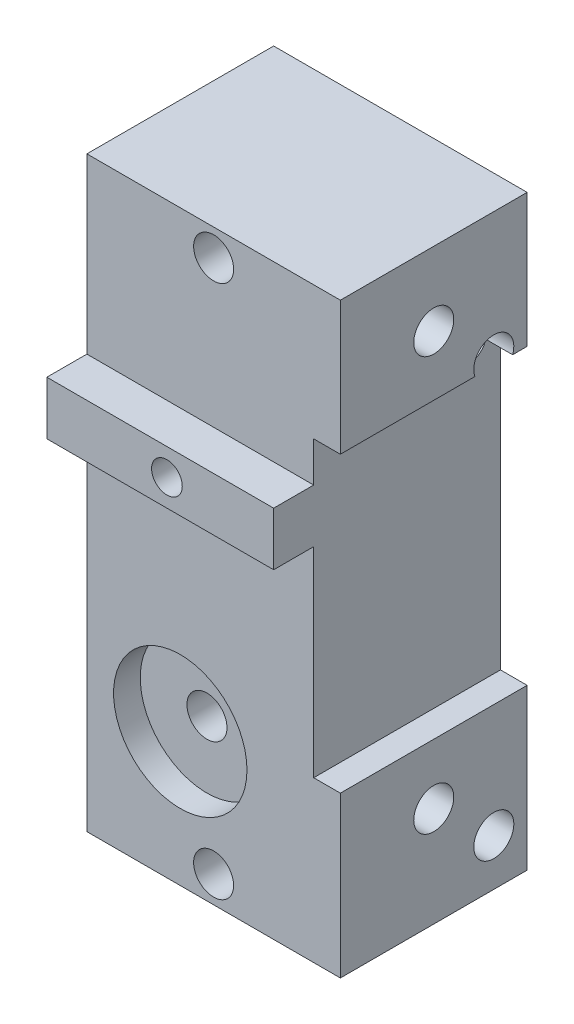
SolidWorks part; units mm, degrees
ref_plane "Front Plane" through (0, 0, 0) normal (0, 0, 1) x (1, 0, 0)
ref_plane "Top Plane" through (0, 0, 0) normal (0, 1, 0) x (1, 0, 0)
ref_plane "Right Plane" through (0, 0, 0) normal (1, 0, 0) x (0, 0, -1)
sketch "Sketch1" plane through (0, 0, 0) normal (0, 0, 1) x (1, 0, 0)
  line L0 (9.5, 0) -> (-9.5, 0)
  line L1 (-9.5, 0) -> (-9.5, 44)
  line L2 (0, 0) -> (0, 74.8611) construction
  line L3 (-9.5, 44) -> (9.5, 44)
  line L4 (9.5, 0) -> (9.5, 44)
  point P8 (0, 44)
  dimension "D1" = 9.5
  dimension "D2" = 44
extrude "Boss-Extrude1" add sketch "Sketch1" along normal blind 14
sketch "Sketch2" plane through (0, 0, 0) normal (0, 0, 1) x (1, 0, 0)
  line L0 (0, 0) -> (0, 44) construction
  line L1 (-9.5, 0) -> (9.5, 0) construction
  line L2 (9.5, 44) -> (-9.5, 44) construction
  line L3 (0, 22) -> (-9.5, 22) construction
  line L4 (-9.5, 44) -> (-9.5, 0) construction
  circle A0 centre (0, 2) radius 1.5
  circle A1 centre (0, 42) radius 1.5
  point P10 (0, 2)
  dimension "D2" = 3
  dimension "D1" = 2
extrude "Cut-Extrude1" cut sketch "Sketch2" against normal through all and the other way through all
sketch "Sketch3" plane through (0, 0, 0) normal (1, 0, 0) x (0, 0, -1)
  line L0 (-14, 0) -> (-7, 0) construction
  line L1 (-14, 0) -> (0, 0) construction
  line L2 (-7, 0) -> (-7, 7.5) construction
  line L3 (-7, 44) -> (-7, 38.5) construction
  line L4 (0, 3.5) -> (-2.5, 3.5) construction
  line L5 (-14, 44) -> (0, 44) construction
  line L6 (0, 0) -> (0, 3.5) construction
  line L7 (0, 44) -> (0, 34.5) construction
  line L8 (0, 44) -> (0, 0) construction
  line L9 (0, 34.5) -> (-2.5, 34.5) construction
  circle A0 centre (-7, 7.5) radius 1.5
  circle A1 centre (-7, 38.5) radius 1.5
  circle A2 centre (-2.5, 3.5) radius 1.5
  circle A3 centre (-2.5, 34.5) radius 1.5
  dimension "D3" = 3
  dimension "D5" = 3
  dimension "D9" = 3
  dimension "D10" = 2.5
  dimension "D11" = 3
  dimension "D1" = 7
  dimension "D2" = 7.5
  dimension "D4" = 5.5
  dimension "D6" = 3.5
  dimension "D7" = 9.5
  dimension "D8" = 2.5
extrude "Cut-Extrude2" cut sketch "Sketch3" along normal blind 20 from surface at -9.5 starting at face at (-9.5, 22, 7)
sketch "Sketch4" plane through (0, 0, 0) normal (0, 0, 1) x (1, 0, 0)
  line L0 (9.5, 27) -> (-9.5, 27)
  line L1 (9.5, 0) -> (9.5, 44) construction
  line L2 (-9.5, 44) -> (-9.5, 0) construction
  line L3 (-9.5, 27) -> (-9.5, 31)
  line L4 (-9.5, 31) -> (9.5, 31)
  line L5 (9.5, 31) -> (9.5, 27)
  dimension "D1" = 17
  dimension "D2" = 4
extrude "Boss-Extrude2" add sketch "Sketch4" along normal blind 3 from surface at 14 starting at face at (1.5, 2, 14)
sketch "Sketch5" plane through (0, 0, 0) normal (0, 0, 1) x (1, 0, 0)
  line L0 (-9.5, 29) -> (-0.5, 29) construction
  line L1 (-9.5, 31) -> (-9.5, 27) construction
  circle A0 centre (-0.5, 29) radius 1.15
  dimension "D2" = 2.3
  dimension "D1" = 9
extrude "Cut-Extrude3" cut sketch "Sketch5" against normal blind 7.5 from surface at 17 starting at face at (0, 29, 17)
sketch "Sketch6" plane through (0, 0, 0) normal (0, 0, 1) x (1, 0, 0)
  circle A0 centre (-0.5, 29) radius 3
  dimension "D1" = 6
extrude "Cut-Extrude4" cut sketch "Sketch6" along normal blind 9.5
sketch "Sketch7" plane through (0, 0, 0) normal (0, 0, 1) x (1, 0, 0)
  line L0 (9.5, 34) -> (7.5, 34)
  line L1 (9.5, 31) -> (9.5, 44) construction
  line L2 (7.5, 34) -> (7.5, 12)
  line L3 (7.5, 12) -> (9.5, 12)
  line L4 (9.5, 0) -> (9.5, 27) construction
  line L5 (-9.5, 0) -> (9.5, 0) construction
  dimension "D1" = 10
  dimension "D2" = 2
  dimension "D3" = 12
extrude "Cut-Extrude5" cut sketch "Sketch7" against normal through all and the other way through all
sketch "Sketch8" plane through (0, 0, 0) normal (0, 0, -1) x (-1, 0, 0)
  line L0 (9.5, 0) -> (-9.5, 0) construction
  line L1 (9.5, 44) -> (9.5, 0) construction
  circle A0 centre (2.5, 10) radius 1.5
  dimension "D3" = 3
  dimension "D1" = 10
  dimension "D2" = 7
extrude "Cut-Extrude6" cut sketch "Sketch8" against normal blind 36
sketch "Sketch9" plane through (0, 0, 14) normal (0, 0, 1) x (1, 0, 0)
  circle A0 centre (-2.5, 10) radius 5
  dimension "D1" = 10
extrude "Cut-Extrude7" cut sketch "Sketch9" against normal blind 2
